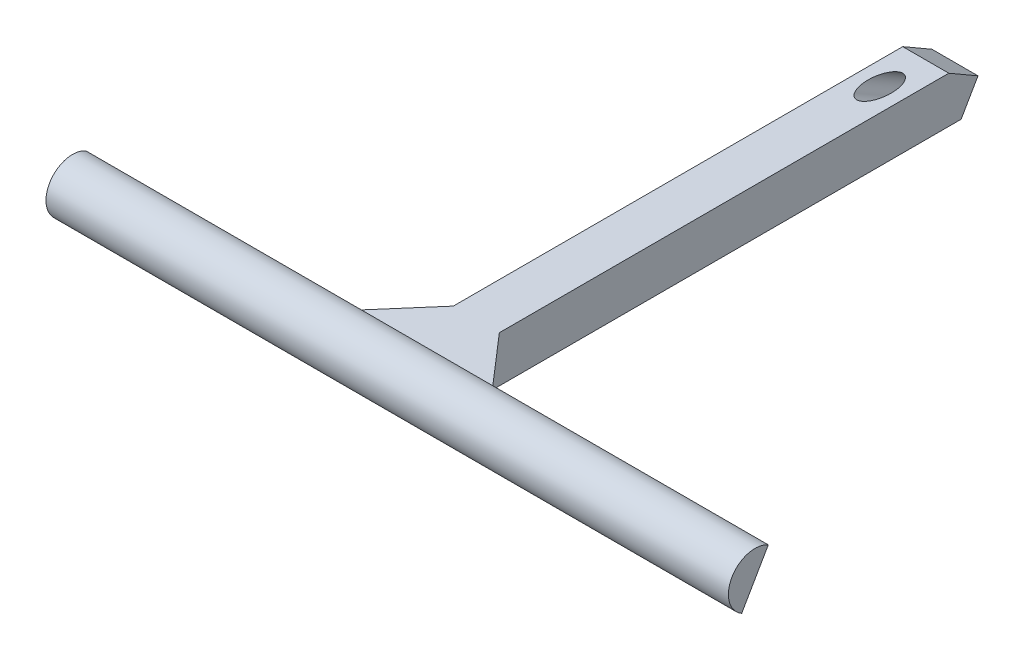
SolidWorks part; units mm, degrees
ref_plane "前视基准面" through (0, 0, 0) normal (0, 0, 1) x (1, 0, 0)
ref_plane "上视基准面" through (0, 0, 0) normal (0, 1, 0) x (1, 0, 0)
ref_plane "右视基准面" through (0, 0, 0) normal (1, 0, 0) x (0, 0, -1)
sketch "草图1" plane through (0, 0, 0) normal (0, 1, 0) x (1, 0, 0)
  line L1 (2.7, -32.5) -> (-2.7, -32.5)
  line L2 (2.7, -32.5) -> (2.7, 32.5)
  line L3 (2.7, 32.5) -> (-2.7, 32.5)
  line L4 (-2.7, -32.5) -> (-2.7, 32.5)
  line L5 (2.7, -32.5) -> (-2.7, 32.5) construction
  line L6 (2.7, 32.5) -> (-2.7, -32.5) construction
  point P0 (0, 0)
  point P6 (0, -24)
  dimension "D1" = 5.4
  dimension "D2" = 65
extrude "凸台-拉伸1" add sketch "草图1" along normal mid plane 5.4
sketch "草图3" plane through (0, 0, 0) normal (1, 0, 0) x (0, 0, -1)
  line L0 (32.5, 0.7235) -> (29.0765, 2.7)
  line L2 (-32.5, 2.7) -> (32.5, 2.7) construction
  line L3 (29.0765, 2.7) -> (27.1, -0.7235)
  line L4 (27.1, -0.7235) -> (30.5235, -2.7)
  line L5 (-32.5, -2.7) -> (32.5, -2.7) construction
  line L6 (30.5235, -2.7) -> (32.5, 0.7235)
  line L7 (29.0765, 2.7) -> (32.5, 2.7)
  line L8 (32.5, 2.7) -> (32.5, -2.7)
  line L9 (32.5, -2.7) -> (30.5235, -2.7)
  line L10 (32.5, -2.7) -> (30.5235, -2.7)
  line L11 (29.0765, 2.7) -> (32.5, 2.7)
  point P2 (35, -1.0023)
  dimension "D1" = 30
extrude "切除-拉伸1" cut sketch "草图3" against normal through all both and the other way through all contours L8 L7 L0 | L9 L8 L6
sketch "草图4" plane through (0, 0, 0) normal (1, 0, 0) x (0, 0, -1)
  line L0 (-32.5, -2.7) -> (-29.3823, 2.7)
  line L1 (30.5235, -2.7) -> (32.5, 0.7235) construction
  circle A0 centre (-30.9412, 0) radius 3.1177
  point P8 (0, 0)
  point P9 (0, 0)
  point P10 (0, 0)
extrude "凸台-拉伸2" add sketch "草图4" along normal mid plane 80 contours L0 A0
chamfer "倒角1" distance 5 angle 45 2 edges at (-2.7, 0, 30.9412) (2.7, 0, 30.9412)
sketch "草图6" plane through (0, -13.892, -24.0617) normal (0, -0.5, -0.866) x (-1, 0, 0)
  line L0 (2.7, 12.9235) -> (2.7, 16.8765) construction
  line L2 (2.7, 16.8765) -> (-2.7, 16.8765) construction
  circle A0 centre (0, 14.1765) radius 1.35
  point P7 (0.8782, 16.8765)
  dimension "D1" = 2.7
  dimension "D2" = 2.7
  dimension "D3" = 2.7
extrude "切除-拉伸2" cut sketch "草图6" against normal through all both and the other way through all
